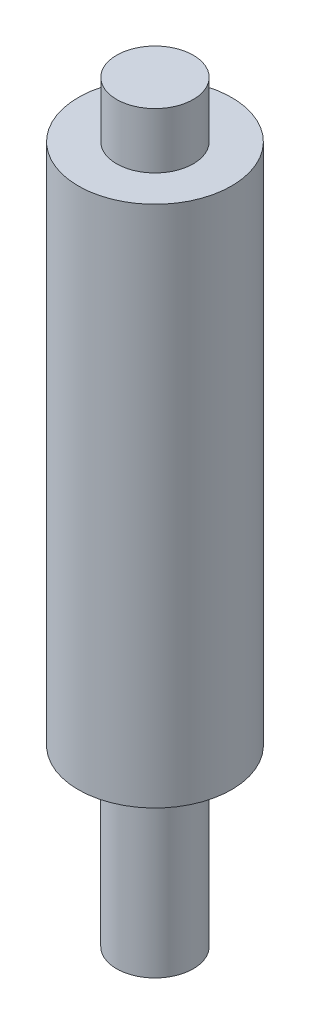
SolidWorks part; units mm, degrees
ref_plane "Front Plane" through (0, 0, 0) normal (0, 0, 1) x (1, 0, 0)
ref_plane "Top Plane" through (0, 0, 0) normal (0, 1, 0) x (1, 0, 0)
ref_plane "Right Plane" through (0, 0, 0) normal (1, 0, 0) x (0, 0, -1)
sketch "Sketch1" plane through (0, 0, 0) normal (0, 1, 0) x (1, 0, 0)
  circle A0 centre (0, 0) radius 2.2
  dimension "D1" = 4.4
extrude "Boss-Extrude1" add sketch "Sketch1" along normal blind 15
sketch "Sketch2" plane through (0, 15, 0) normal (0, 1, 0) x (1, 0, 0)
  circle A0 centre (0, 0) radius 1.1
  dimension "D1" = 2.2
extrude "Boss-Extrude2" add sketch "Sketch2" along normal blind 1.6
sketch "Sketch3" plane through (0, 0, 0) normal (0, -1, 0) x (1, 0, 0)
  circle A0 centre (0, 0) radius 1.1
  dimension "D1" = 2.2
extrude "Boss-Extrude3" add sketch "Sketch3" along normal blind 5
